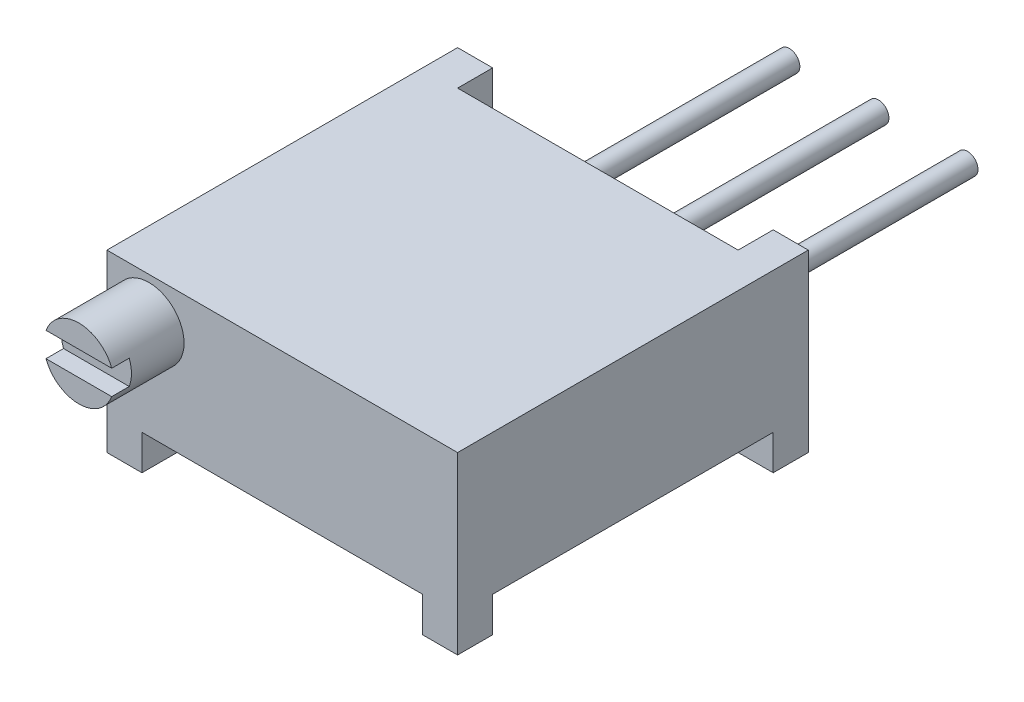
SolidWorks part; units mm, degrees
ref_plane "Спереди" through (0, 0, 0) normal (0, 0, 1) x (1, 0, 0)
ref_plane "Сверху" through (0, 0, 0) normal (0, 1, 0) x (1, 0, 0)
ref_plane "Справа" through (0, 0, 0) normal (1, 0, 0) x (0, 0, -1)
ref_plane "Плоскость1" through (-5, 0, 0) normal (-1, 0, 0) x (0, -1, 0)
sketch "Эскиз1" plane through (-5, 0, 0) normal (-1, 0, 0) x (0, -1, 0)
  line L0 (2.41, 0) -> (2.41, 10)
  line L1 (2.41, 10) -> (-2.59, 10)
  line L2 (-2.59, 10) -> (-2.59, 0)
  line L3 (-2.59, 0) -> (2.41, 0)
extrude "Бобышка-Вытянуть1" add sketch "Эскиз1" against normal blind 1
sketch "Эскиз2" plane through (-4, 0, 0) normal (1, 0, 0) x (0, 0, -1)
  line L0 (-1, -1.41) -> (-10, -1.41)
  line L1 (-10, -1.41) -> (-10, -2.41)
  line L2 (-10, -2.41) -> (-1, -2.41)
  line L3 (-1, -2.41) -> (-1, -1.41)
extrude "Вырез-Вытянуть1" cut sketch "Эскиз2" against normal through all
sketch "Эскиз3" plane through (-4, 0, 0) normal (1, 0, 0) x (0, 0, -1)
  line L0 (-1, 2.59) -> (-1, -1.41)
  line L1 (-1, -1.41) -> (-10, -1.41)
  line L2 (-10, -1.41) -> (-10, 2.59)
  line L3 (-10, 2.59) -> (-1, 2.59)
extrude "Бобышка-Вытянуть2" add sketch "Эскиз3" along normal blind 9
sketch "Эскиз4" plane through (0, 0, 1) normal (0, 0, -1) x (-1, 0, 0)
  line L0 (-4, -1.41) -> (-5, -1.41)
  line L1 (-5, -1.41) -> (-5, 2.59)
  line L2 (-5, 2.59) -> (-4, 2.59)
  line L3 (-4, 2.59) -> (-4, -1.41)
extrude "Бобышка-Вытянуть3" add sketch "Эскиз4" along normal blind 1
sketch "Эскиз5" plane through (0, -1.41, 0) normal (0, -1, 0) x (1, 0, 0)
  line L0 (4, 1) -> (5, 1)
  line L1 (5, 1) -> (5, 0)
  line L2 (5, 0) -> (4, 0)
  line L3 (4, 0) -> (4, 1)
extrude "Бобышка-Вытянуть4" add sketch "Эскиз5" along normal blind 1
sketch "Эскиз6" plane through (0, -1.41, 0) normal (0, -1, 0) x (1, 0, 0)
  line L0 (-5, 10) -> (-4, 10)
  line L1 (-4, 10) -> (-4, 9)
  line L2 (-4, 9) -> (-5, 9)
  line L3 (-5, 9) -> (-5, 10)
extrude "Бобышка-Вытянуть5" add sketch "Эскиз6" along normal blind 1
sketch "Эскиз7" plane through (0, -1.41, 0) normal (0, -1, 0) x (1, 0, 0)
  line L0 (4, 10) -> (5, 10)
  line L1 (5, 10) -> (5, 9)
  line L2 (5, 9) -> (4, 9)
  line L3 (4, 9) -> (4, 10)
extrude "Бобышка-Вытянуть6" add sketch "Эскиз7" along normal blind 1
sketch "Эскиз8" plane through (0, 0, 10) normal (0, 0, 1) x (1, 0, 0)
  circle A0 centre (-3.8, 1.39) radius 1
extrude "Бобышка-Вытянуть7" add sketch "Эскиз8" along normal blind 2
sketch "Эскиз9" plane through (0, 0, 12) normal (0, 0, 1) x (1, 0, 0)
  line L0 (-4.7367, 1.04) -> (-2.8633, 1.04)
  arc A0 (-2.8633, 1.04) -> (-4.7367, 1.04) centre (-3.8, 1.39) ccw
extrude "Вырез-Вытянуть2" cut sketch "Эскиз9" against normal blind 0.5
sketch "Эскиз10" plane through (0, 0, 11.5) normal (0, 0, 1) x (1, 0, 0)
  line L0 (-2.8633, 1.74) -> (-4.7367, 1.74)
  arc A0 (-4.7367, 1.74) -> (-2.8633, 1.74) centre (-3.8, 1.39) cw
extrude "Бобышка-Вытянуть8" add sketch "Эскиз10" along normal blind 0.5
sketch "Эскиз11" plane through (0, 0, 1) normal (0, 0, -1) x (-1, 0, 0)
  circle A0 centre (-2.54, 0) radius 0.3
extrude "Бобышка-Вытянуть9" add sketch "Эскиз11" along normal blind 8
sketch "Эскиз12" plane through (0, 0, 1) normal (0, 0, -1) x (-1, 0, 0)
  circle A0 centre (0, 0) radius 0.3
extrude "Бобышка-Вытянуть10" add sketch "Эскиз12" along normal blind 8
sketch "Эскиз13" plane through (0, 0, 1) normal (0, 0, -1) x (-1, 0, 0)
  circle A0 centre (2.54, 0) radius 0.3
extrude "Бобышка-Вытянуть11" add sketch "Эскиз13" along normal blind 8
